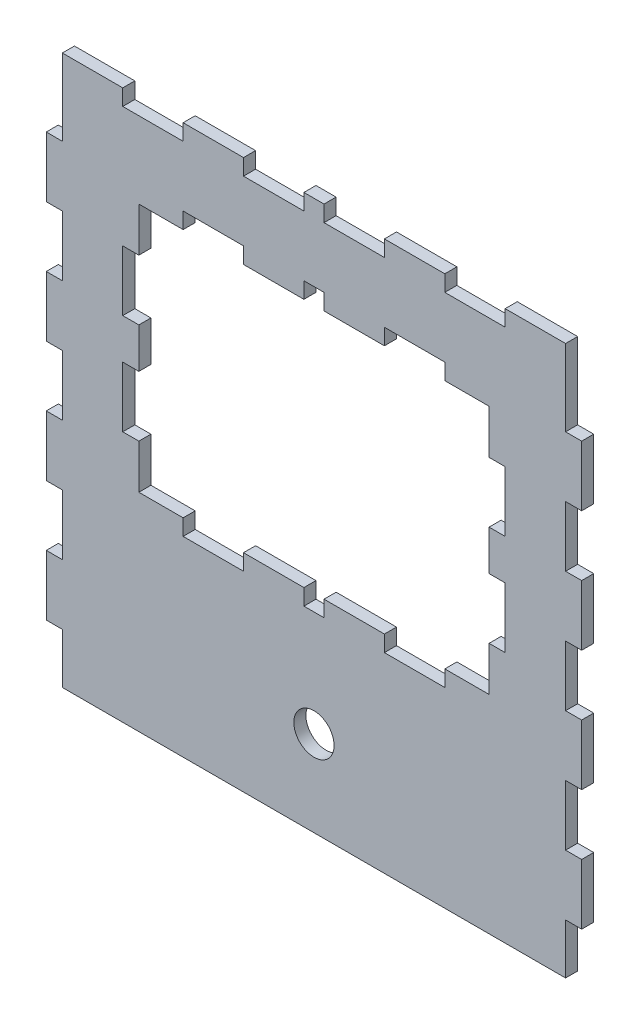
SolidWorks part; units mm, degrees
ref_plane "Front Plane" through (0, 0, 0) normal (0, 0, 1) x (1, 0, 0)
ref_plane "Top Plane" through (0, 0, 0) normal (0, 1, 0) x (1, 0, 0)
ref_plane "Right Plane" through (0, 0, 0) normal (1, 0, 0) x (0, 0, -1)
sketch "Sketch1" plane through (0, 0, 0) normal (0, 0, 1) x (1, 0, 0)
  line L0 (-110, 47.5) -> (-15, 47.5)
  line L1 (0, 0) -> (-125, 0)
  line L2 (0, 0) -> (0, 132.5)
  line L3 (0, 132.5) -> (-125, 132.5)
  line L4 (-125, 0) -> (-125, 132.5)
  line L5 (-15, 47.5) -> (-15, 117.5)
  line L6 (-15, 117.5) -> (-110, 117.5)
  line L7 (-110, 117.5) -> (-110, 47.5)
  dimension "D1" = 132.5
  dimension "D2" = 125
  dimension "D3" = 15
  dimension "D4" = 15
extrude "Boss-Extrude1" add sketch "Sketch1" along normal blind 3
sketch "Sketch2" plane through (0, 0, 3) normal (0, 0, 1) x (1, 0, 0)
  line L8 (-75, 27.5) -> (-50, 15) construction
  line L9 (-50, 27.5) -> (-75, 15) construction
  circle A0 centre (-62.5, 21.25) radius 5
  dimension "D1" = 10
extrude "Cut-Extrude1" cut sketch "Sketch2" against normal blind 10
sketch "Sketch3" plane through (0, 0, 3) normal (0, 0, 1) x (1, 0, 0)
  line L0 (-60, 136.5) -> (-65, 136.5)
  line L2 (4, 0) -> (4, 132.5)
  line L3 (4, 12.5) -> (4, 27.5)
  line L4 (0, 117.5) -> (0, 102.5)
  line L6 (0, 117.5) -> (4, 117.5)
  line L7 (0, 102.5) -> (4, 102.5)
  line L8 (0, 87.5) -> (4, 87.5)
  line L9 (0, 72.5) -> (4, 72.5)
  line L10 (0, 57.5) -> (4, 57.5)
  line L11 (0, 42.5) -> (4, 42.5)
  line L12 (0, 27.5) -> (4, 27.5)
  line L13 (0, 12.5) -> (4, 12.5)
  line L14 (4, 42.5) -> (4, 57.5)
  line L15 (0, 27.5) -> (0, 12.5)
  line L16 (4, 72.5) -> (4, 87.5)
  line L17 (0, 57.5) -> (0, 42.5)
  line L18 (4, 102.5) -> (4, 117.5)
  line L19 (0, 87.5) -> (0, 72.5)
  line L22 (-95, 117.5) -> (-95, 113.5)
  line L23 (-125, 87.5) -> (-125, 72.5)
  line L24 (-129, 102.5) -> (-129, 117.5)
  line L25 (-125, 57.5) -> (-125, 42.5)
  line L26 (-129, 72.5) -> (-129, 87.5)
  line L27 (-125, 27.5) -> (-125, 12.5)
  line L28 (-129, 42.5) -> (-129, 57.5)
  line L29 (-125, 12.5) -> (-129, 12.5)
  line L30 (-125, 27.5) -> (-129, 27.5)
  line L31 (-125, 42.5) -> (-129, 42.5)
  line L32 (-125, 57.5) -> (-129, 57.5)
  line L33 (-125, 72.5) -> (-129, 72.5)
  line L34 (-125, 87.5) -> (-129, 87.5)
  line L35 (-125, 102.5) -> (-129, 102.5)
  line L36 (-125, 117.5) -> (-129, 117.5)
  line L37 (-125, 117.5) -> (-125, 102.5)
  line L38 (-129, 12.5) -> (-129, 27.5)
  line L39 (-60, 132.5) -> (-65, 132.5)
  line L40 (-125, 136.5) -> (-125, 132.5)
  line L41 (0, 136.5) -> (-125, 136.5)
  line L42 (0, 136.5) -> (-15, 136.5)
  line L43 (0, 136.5) -> (0, 132.5)
  line L44 (0, 132.5) -> (-15, 132.5)
  line L45 (-15, 136.5) -> (-15, 132.5)
  line L46 (-30, 136.5) -> (-30, 132.5)
  line L47 (-45, 136.5) -> (-45, 132.5)
  line L48 (-60, 136.5) -> (-60, 132.5)
  line L49 (-65, 136.5) -> (-65, 132.5)
  line L50 (-80, 136.5) -> (-80, 132.5)
  line L51 (-95, 136.5) -> (-95, 132.5)
  line L52 (-110, 136.5) -> (-110, 132.5)
  line L53 (-110, 136.5) -> (-125, 136.5)
  line L54 (-110, 132.5) -> (-125, 132.5)
  line L55 (-80, 136.5) -> (-95, 136.5)
  line L56 (-80, 132.5) -> (-95, 132.5)
  line L57 (-30, 136.5) -> (-45, 136.5)
  line L58 (-30, 132.5) -> (-45, 132.5)
  line L59 (-15, 113.5) -> (-110, 113.5)
  line L60 (-15, 113.5) -> (-30, 113.5)
  line L61 (-15, 117.5) -> (-110, 117.5) construction
  line L62 (-80, 117.5) -> (-80, 113.5)
  line L63 (-65, 117.5) -> (-65, 113.5)
  line L64 (-60, 117.5) -> (-60, 113.5)
  line L65 (-45, 117.5) -> (-45, 113.5)
  line L66 (-30, 117.5) -> (-30, 113.5)
  line L67 (-15, 117.5) -> (-15, 113.5)
  line L68 (-110, 117.5) -> (-110, 113.5)
  line L69 (-110, 117.5) -> (-95, 117.5)
  line L70 (-80, 117.5) -> (-65, 117.5)
  line L71 (-95, 113.5) -> (-110, 113.5)
  line L72 (-60, 117.5) -> (-45, 117.5)
  line L73 (-65, 113.5) -> (-80, 113.5)
  line L74 (-30, 117.5) -> (-15, 117.5)
  line L75 (-45, 113.5) -> (-60, 113.5)
  line L76 (-110, 82.5) -> (-15, 82.5) construction
  line L77 (-110, 117.5) -> (-110, 47.5) construction
  line L78 (-15, 47.5) -> (-15, 117.5) construction
  line L79 (-45, 51.5) -> (-60, 51.5)
  line L80 (-30, 47.5) -> (-15, 47.5)
  line L81 (-65, 51.5) -> (-80, 51.5)
  line L82 (-60, 47.5) -> (-45, 47.5)
  line L83 (-95, 51.5) -> (-110, 51.5)
  line L84 (-80, 47.5) -> (-65, 47.5)
  line L85 (-110, 47.5) -> (-95, 47.5)
  line L86 (-110, 47.5) -> (-110, 51.5)
  line L87 (-15, 47.5) -> (-15, 51.5)
  line L88 (-30, 47.5) -> (-30, 51.5)
  line L89 (-45, 47.5) -> (-45, 51.5)
  line L90 (-60, 47.5) -> (-60, 51.5)
  line L91 (-65, 47.5) -> (-65, 51.5)
  line L92 (-80, 47.5) -> (-80, 51.5)
  line L93 (-15, 51.5) -> (-30, 51.5)
  line L94 (-95, 47.5) -> (-95, 51.5)
  dimension "D2" = 4
  dimension "D3" = 15
  dimension "D4" = 15
  dimension "D5" = 15
  dimension "D6" = 15
  dimension "D7" = 15
  dimension "D8" = 15
  dimension "D9" = 15
  dimension "D10" = 15
  dimension "D11" = 15
  dimension "D12" = 15
  dimension "D13" = 15
  dimension "D14" = 15
  dimension "D15" = 15
  dimension "D16" = 15
  dimension "D17" = 15
  dimension "D1" = 4
  dimension "D18" = 4
extrude "Boss-Extrude2" add sketch "Sketch3" against normal blind 3
sketch "Sketch4" plane through (0, 0, 3) normal (0, 0, 1) x (1, 0, 0)
  line L0 (-106, 87.5) -> (-106, 77.5)
  line L1 (-106, 113.5) -> (-110, 113.5)
  line L2 (-106, 113.5) -> (-106, 51.5)
  line L3 (-106, 113.5) -> (-106, 102.5)
  line L4 (-110, 113.5) -> (-110, 102.5)
  line L5 (-110, 51.5) -> (-106, 51.5)
  line L6 (-110, 102.5) -> (-106, 102.5)
  line L7 (-110, 87.5) -> (-106, 87.5)
  line L8 (-110, 77.5) -> (-106, 77.5)
  line L9 (-110, 62.5) -> (-106, 62.5)
  line L10 (-110, 87.5) -> (-110, 77.5)
  line L11 (-106, 62.5) -> (-106, 51.5)
  line L12 (-110, 62.5) -> (-110, 51.5)
  line L13 (-62.5, 117.5) -> (-62.5, 47.5) construction
  line L14 (-60, 117.5) -> (-65, 117.5) construction
  line L15 (-65, 47.5) -> (-60, 47.5) construction
  line L16 (-15, 62.5) -> (-15, 51.5)
  line L17 (-19, 62.5) -> (-19, 51.5)
  line L18 (-15, 87.5) -> (-15, 77.5)
  line L19 (-15, 62.5) -> (-19, 62.5)
  line L20 (-15, 77.5) -> (-19, 77.5)
  line L21 (-15, 87.5) -> (-19, 87.5)
  line L22 (-15, 102.5) -> (-19, 102.5)
  line L23 (-15, 51.5) -> (-19, 51.5)
  line L24 (-15, 113.5) -> (-15, 102.5)
  line L25 (-19, 113.5) -> (-19, 102.5)
  line L26 (-19, 113.5) -> (-15, 113.5)
  line L27 (-19, 87.5) -> (-19, 77.5)
  dimension "D2" = 11
  dimension "D3" = 15
  dimension "D4" = 11
  dimension "D5" = 15
  dimension "D1" = 4
extrude "Boss-Extrude3" add sketch "Sketch4" against normal blind 3
